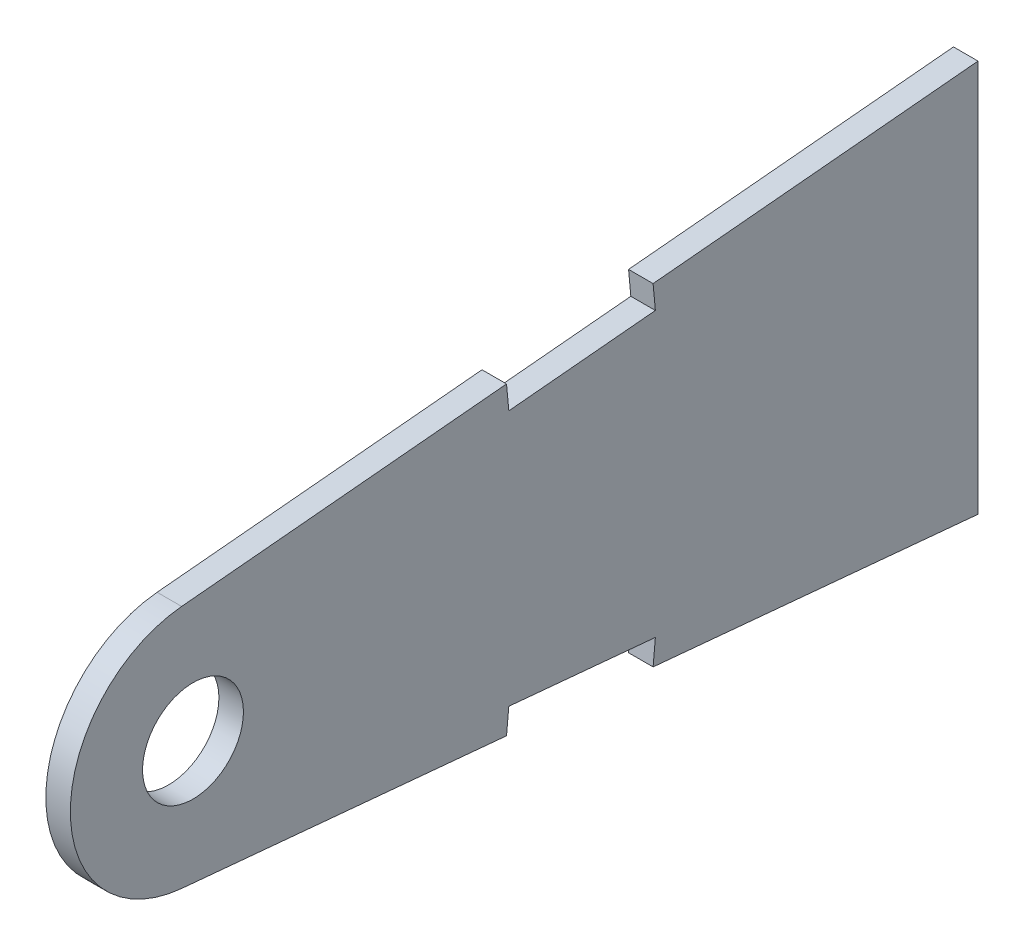
SolidWorks part; units mm, degrees
material "AISI 4130 Steel, annealed at 865C"
ref_plane "X-Y Datum" through (0, 0, 0) normal (0, 0, 1) x (1, 0, 0)
ref_plane "X-Z Datum" through (0, 0, 0) normal (0, 1, 0) x (1, 0, 0)
ref_plane "Y-Z Datum" through (0, 0, 0) normal (1, 0, 0) x (0, 0, -1)
sketch "Sketch1" plane through (0, 0, 0) normal (1, 0, 0) x (0, 0, -1)
  line L0 (-0.7356, -7.9033) -> (50.8, -12.7)
  line L1 (50.8, -12.7) -> (50.8, 12.7)
  line L2 (50.8, 12.7) -> (-0.7356, 7.9033)
  line L3 (-7.9375, 0) -> (50.8, 0) construction
  line L4 (20.2902, -9.8603) -> (29.7742, -10.743)
  line L5 (20.2902, -9.8603) -> (20.4373, -8.2796)
  line L6 (29.7742, -10.743) -> (29.9213, -9.1624)
  line L7 (20.4373, -8.2796) -> (29.9213, -9.1624)
  line L8 (29.7742, 10.743) -> (29.9213, 9.1624)
  line L9 (20.4373, 8.2796) -> (29.9213, 9.1624)
  line L10 (20.2902, 9.8603) -> (20.4373, 8.2796)
  arc A0 (-0.7356, 7.9033) -> (-0.7356, -7.9033) centre (0, 0) ccw
  point P1 (50.8, 0)
  point P9 (25.0322, -10.3017)
  point P10 (25.0322, -10.3017)
  dimension "D1" = 7.9375
  dimension "D2" = 25.4
  dimension "D3" = 1.5875
  dimension "D4" = 9.525
  dimension "D5" = 50.8
extrude "Boss-Extrude1" add sketch "Sketch1" along normal blind 1.5875 contours A0 L3 L1 L2 L8 L9 L10 | L3 A0 L0 L5 L7 L6 L1
hole_wizard "1/4 Clearance Hole1" positions "Sketch2" profile "Sketch3" hole size "1/4" standard "ANSI Inch" end condition through all
sketch "Sketch2" plane through (1.5875, 0, 0) normal (1, 0, 0) x (0, 0, -1)
  point P0 (0, 0)
sketch "Sketch3" plane through (1.5875, 0, 0) normal (0, 1, 0) x (0, 0, -1)
  line L0 (0, 0) -> (0, 1.5875)
  line L1 (0, 1.5875) -> (3.2639, 1.5875)
  line L2 (3.2639, 1.5875) -> (3.2639, 0)
  line L5 (3.2639, 0) -> (0, 0)
  line L11 (0, -6.35) -> (0, 107.95) construction
  dimension "Thru Hole Dia." = 6.5278
  dimension "Thru Hole Depth" = 1.5875
